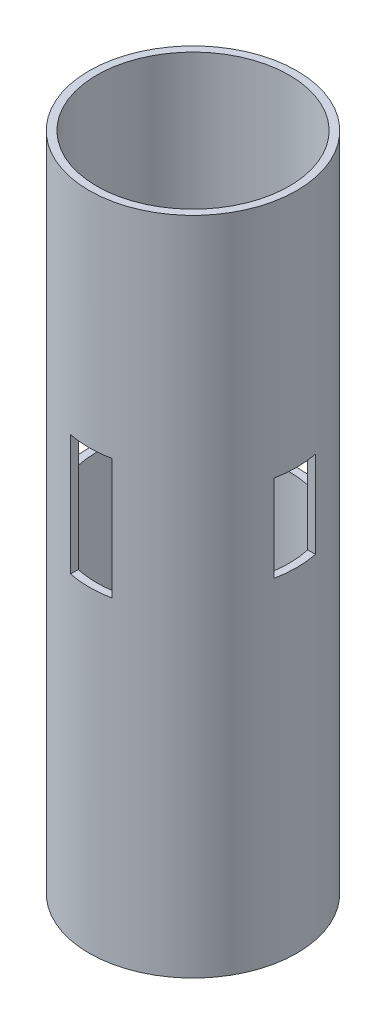
SolidWorks part; units mm, degrees
ref_plane "Front Plane" through (0, 0, 0) normal (0, 0, 1) x (1, 0, 0)
ref_plane "Top Plane" through (0, 0, 0) normal (0, 1, 0) x (1, 0, 0)
ref_plane "Right Plane" through (0, 0, 0) normal (1, 0, 0) x (0, 0, -1)
sketch "Sketch1" plane through (0, 0, 0) normal (0, 1, 0) x (1, 0, 0)
  circle A0 centre (0, 0) radius 25.5
  circle A1 centre (0, 0) radius 27.5
  dimension "D1" = 51
  dimension "D2" = 55
extrude "Boss-Extrude1" add sketch "Sketch1" along normal blind 175
sketch "Sketch3" plane through (0, 0, 0) normal (1, 0, 0) x (0, 0, -1)
  line L0 (0, 0) -> (0, 100)
  line L2 (-5.5, 111.5) -> (5.5, 111.5)
  line L3 (-5.5, 111.5) -> (-5.5, 88.5)
  line L4 (-5.5, 88.5) -> (5.5, 88.5)
  line L5 (5.5, 111.5) -> (5.5, 88.5)
  line L6 (-5.5, 111.5) -> (5.5, 88.5) construction
  line L7 (-5.5, 88.5) -> (5.5, 111.5) construction
  dimension "D1" = 100
  dimension "D2" = 23
  dimension "D3" = 11
extrude "Cut-Extrude1" cut sketch "Sketch3" against normal through all and the other way through all
sketch "Sketch4" plane through (0, 0, 0) normal (0, 0, 1) x (1, 0, 0)
  line L0 (0, 0) -> (0, 100)
  line L2 (5.5, 116) -> (-5.5, 116)
  line L3 (5.5, 116) -> (5.5, 84)
  line L4 (5.5, 84) -> (-5.5, 84)
  line L5 (-5.5, 116) -> (-5.5, 84)
  line L6 (5.5, 116) -> (-5.5, 84) construction
  line L7 (5.5, 84) -> (-5.5, 116) construction
  dimension "D1" = 100
  dimension "D2" = 11
  dimension "D3" = 32
extrude "Cut-Extrude2" cut sketch "Sketch4" against normal through all and the other way through all
